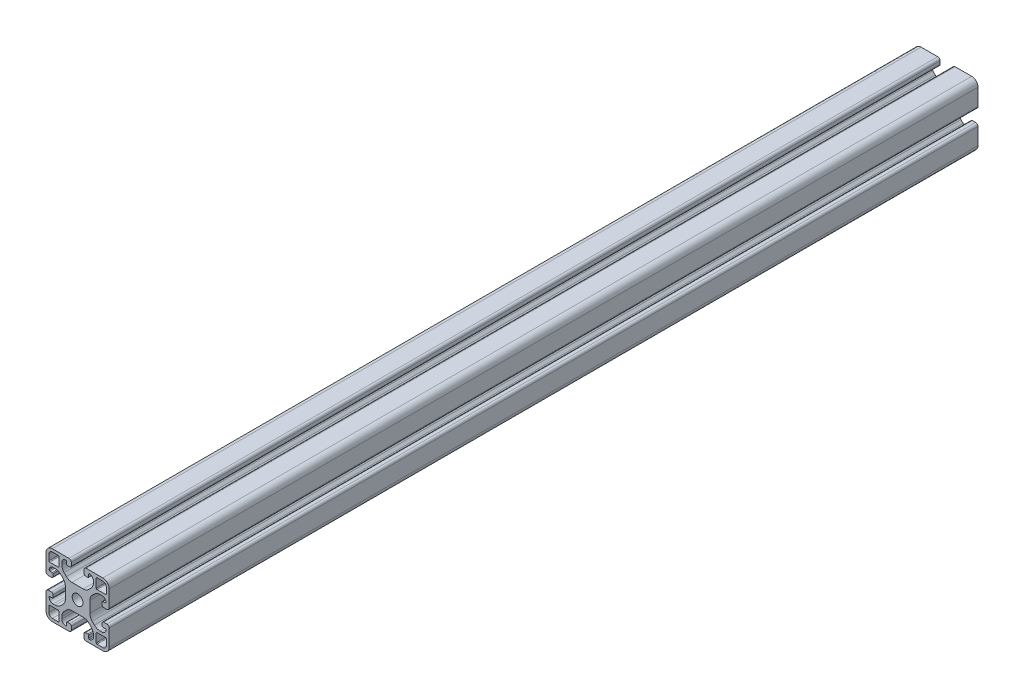
SolidWorks part; units mm, degrees
ref_plane "Plan de face" through (0, 0, 0) normal (0, 0, 1) x (1, 0, 0)
ref_plane "Plan de dessus" through (0, 0, 0) normal (0, 1, 0) x (1, 0, 0)
ref_plane "Plan de droite" through (0, 0, 0) normal (1, 0, 0) x (0, 0, -1)
ref_plane "Plan1" through (0, 0, -30) normal (0, 0, -1) x (-1, 0, 0)
sketch "Esquisse1" plane through (0, 0, -30) normal (0, 0, -1) x (-1, 0, 0)
  line L0 (-4.5, 15) -> (-4.5, 13.5)
  line L1 (-4, 13) -> (-2.5, 13)
  line L2 (-4.5, 10) -> (-5.8076, 10)
  line L3 (-9.3431, 11.4645) -> (-10.7855, 12.9069)
  line L4 (-12.25, 16.4424) -> (-12.25, 23.5576)
  line L5 (-10.7855, 27.0931) -> (-9.3431, 28.5355)
  line L6 (-5.8076, 30) -> (-4.5, 30)
  line L7 (-2.5, 27) -> (-4, 27)
  line L8 (-4.5, 26.5) -> (-4.5, 25)
  line L9 (-3.5, 24) -> (-1.5, 24)
  line L10 (0, 25.5) -> (0, 36)
  line L11 (-4, 40) -> (-14.5, 40)
  line L12 (-16, 38.5) -> (-16, 36.5)
  line L13 (-15, 35.5) -> (-13.5, 35.5)
  line L14 (-13, 36) -> (-13, 37.5)
  line L15 (-10, 35.5) -> (-10, 34.1924)
  line L16 (-11.4645, 30.6569) -> (-12.9069, 29.2145)
  line L17 (-16.4424, 27.75) -> (-23.5576, 27.75)
  line L18 (-27.0931, 29.2145) -> (-28.5355, 30.6569)
  line L19 (-30, 34.1924) -> (-30, 35.5)
  line L20 (-27, 37.5) -> (-27, 36)
  line L21 (-26.5, 35.5) -> (-25, 35.5)
  line L22 (-24, 36.5) -> (-24, 38.5)
  line L23 (-25.5, 40) -> (-36, 40)
  line L24 (-40, 36) -> (-40, 25.5)
  line L25 (-38.5, 24) -> (-36.5, 24)
  line L26 (-35.5, 25) -> (-35.5, 26.5)
  line L27 (-36, 27) -> (-37.5, 27)
  line L28 (-35.5, 30) -> (-34.1924, 30)
  line L29 (-30.6569, 28.5355) -> (-29.2145, 27.0931)
  line L30 (-27.75, 23.5576) -> (-27.75, 16.4424)
  line L31 (-29.2145, 12.9069) -> (-30.6569, 11.4645)
  line L32 (-34.1924, 10) -> (-35.5, 10)
  line L33 (-37.5, 13) -> (-36, 13)
  line L34 (-35.5, 13.5) -> (-35.5, 15)
  line L35 (-36.5, 16) -> (-38.5, 16)
  line L36 (-40, 14.5) -> (-40, 4)
  line L37 (-36, 0) -> (-25.5, 0)
  line L38 (-24, 1.5) -> (-24, 3.5)
  line L39 (-25, 4.5) -> (-26.5, 4.5)
  line L40 (-27, 4) -> (-27, 2.5)
  line L41 (-30, 4.5) -> (-30, 5.8076)
  line L42 (-28.5355, 9.3431) -> (-27.0931, 10.7855)
  line L43 (-23.5576, 12.25) -> (-16.4424, 12.25)
  line L44 (-12.9069, 10.7855) -> (-11.4645, 9.3431)
  line L45 (-10, 5.8076) -> (-10, 4.5)
  line L46 (-13, 2.5) -> (-13, 4)
  line L47 (-13.5, 4.5) -> (-15, 4.5)
  line L48 (-16, 3.5) -> (-16, 1.5)
  line L49 (-14.5, 0) -> (-4, 0)
  line L50 (0, 4) -> (0, 14.5)
  line L51 (-1.5, 16) -> (-3.5, 16)
  line L52 (-4, 1.8) -> (-7.7, 1.8)
  line L53 (-8.2, 2.3) -> (-8.2, 7.7)
  line L54 (-7.7, 8.2) -> (-2.3, 8.2)
  line L55 (-1.8, 7.7) -> (-1.8, 4)
  line L56 (-38.2, 4) -> (-38.2, 7.7)
  line L57 (-37.7, 8.2) -> (-32.3, 8.2)
  line L58 (-31.8, 7.7) -> (-31.8, 2.3)
  line L59 (-32.3, 1.8) -> (-36, 1.8)
  line L60 (-36, 38.2) -> (-32.3, 38.2)
  line L61 (-31.8, 37.7) -> (-31.8, 32.3)
  line L62 (-32.3, 31.8) -> (-37.7, 31.8)
  line L63 (-38.2, 32.3) -> (-38.2, 36)
  line L64 (-1.8, 36) -> (-1.8, 32.3)
  line L65 (-2.3, 31.8) -> (-7.7, 31.8)
  line L66 (-8.2, 32.3) -> (-8.2, 37.7)
  line L67 (-7.7, 38.2) -> (-4, 38.2)
  arc A0 (-4.5, 13.5) -> (-4, 13) centre (-4, 13.5) ccw
  arc A1 (-2.5, 13) -> (-2, 12.5) centre (-2.5, 12.5) cw
  arc A2 (-2, 12.5) -> (-4.5, 10) centre (-4.5, 12.5) cw
  arc A3 (-5.8076, 10) -> (-9.3431, 11.4645) centre (-5.8076, 15) cw
  arc A4 (-10.7855, 12.9069) -> (-12.25, 16.4424) centre (-7.25, 16.4424) cw
  arc A5 (-12.25, 23.5576) -> (-10.7855, 27.0931) centre (-7.25, 23.5576) cw
  arc A6 (-9.3431, 28.5355) -> (-5.8076, 30) centre (-5.8076, 25) cw
  arc A7 (-4.5, 30) -> (-2, 27.5) centre (-4.5, 27.5) cw
  arc A8 (-2, 27.5) -> (-2.5, 27) centre (-2.5, 27.5) cw
  arc A9 (-4, 27) -> (-4.5, 26.5) centre (-4, 26.5) ccw
  arc A10 (-4.5, 25) -> (-3.5, 24) centre (-3.5, 25) ccw
  arc A11 (-1.5, 24) -> (0, 25.5) centre (-1.5, 25.5) ccw
  arc A12 (0, 36) -> (-4, 40) centre (-4, 36) ccw
  arc A13 (-14.5, 40) -> (-16, 38.5) centre (-14.5, 38.5) ccw
  arc A14 (-16, 36.5) -> (-15, 35.5) centre (-15, 36.5) ccw
  arc A15 (-13.5, 35.5) -> (-13, 36) centre (-13.5, 36) ccw
  arc A16 (-13, 37.5) -> (-12.5, 38) centre (-12.5, 37.5) cw
  arc A17 (-12.5, 38) -> (-10, 35.5) centre (-12.5, 35.5) cw
  arc A18 (-10, 34.1924) -> (-11.4645, 30.6569) centre (-15, 34.1924) cw
  arc A19 (-12.9069, 29.2145) -> (-16.4424, 27.75) centre (-16.4424, 32.75) cw
  arc A20 (-23.5576, 27.75) -> (-27.0931, 29.2145) centre (-23.5576, 32.75) cw
  arc A21 (-28.5355, 30.6569) -> (-30, 34.1924) centre (-25, 34.1924) cw
  arc A22 (-30, 35.5) -> (-27.5, 38) centre (-27.5, 35.5) cw
  arc A23 (-27.5, 38) -> (-27, 37.5) centre (-27.5, 37.5) cw
  arc A24 (-27, 36) -> (-26.5, 35.5) centre (-26.5, 36) ccw
  arc A25 (-25, 35.5) -> (-24, 36.5) centre (-25, 36.5) ccw
  arc A26 (-24, 38.5) -> (-25.5, 40) centre (-25.5, 38.5) ccw
  arc A27 (-36, 40) -> (-40, 36) centre (-36, 36) ccw
  arc A28 (-40, 25.5) -> (-38.5, 24) centre (-38.5, 25.5) ccw
  arc A29 (-36.5, 24) -> (-35.5, 25) centre (-36.5, 25) ccw
  arc A30 (-35.5, 26.5) -> (-36, 27) centre (-36, 26.5) ccw
  arc A31 (-37.5, 27) -> (-38, 27.5) centre (-37.5, 27.5) cw
  arc A32 (-38, 27.5) -> (-35.5, 30) centre (-35.5, 27.5) cw
  arc A33 (-34.1924, 30) -> (-30.6569, 28.5355) centre (-34.1924, 25) cw
  arc A34 (-29.2145, 27.0931) -> (-27.75, 23.5576) centre (-32.75, 23.5576) cw
  arc A35 (-27.75, 16.4424) -> (-29.2145, 12.9069) centre (-32.75, 16.4424) cw
  arc A36 (-30.6569, 11.4645) -> (-34.1924, 10) centre (-34.1924, 15) cw
  arc A37 (-35.5, 10) -> (-38, 12.5) centre (-35.5, 12.5) cw
  arc A38 (-38, 12.5) -> (-37.5, 13) centre (-37.5, 12.5) cw
  arc A39 (-36, 13) -> (-35.5, 13.5) centre (-36, 13.5) ccw
  arc A40 (-35.5, 15) -> (-36.5, 16) centre (-36.5, 15) ccw
  arc A41 (-38.5, 16) -> (-40, 14.5) centre (-38.5, 14.5) ccw
  arc A42 (-40, 4) -> (-36, 0) centre (-36, 4) ccw
  arc A43 (-25.5, 0) -> (-24, 1.5) centre (-25.5, 1.5) ccw
  arc A44 (-24, 3.5) -> (-25, 4.5) centre (-25, 3.5) ccw
  arc A45 (-26.5, 4.5) -> (-27, 4) centre (-26.5, 4) ccw
  arc A46 (-27, 2.5) -> (-27.5, 2) centre (-27.5, 2.5) cw
  arc A47 (-27.5, 2) -> (-30, 4.5) centre (-27.5, 4.5) cw
  arc A48 (-30, 5.8076) -> (-28.5355, 9.3431) centre (-25, 5.8076) cw
  arc A49 (-27.0931, 10.7855) -> (-23.5576, 12.25) centre (-23.5576, 7.25) cw
  arc A50 (-16.4424, 12.25) -> (-12.9069, 10.7855) centre (-16.4424, 7.25) cw
  arc A51 (-11.4645, 9.3431) -> (-10, 5.8076) centre (-15, 5.8076) cw
  arc A52 (-10, 4.5) -> (-12.5, 2) centre (-12.5, 4.5) cw
  arc A53 (-12.5, 2) -> (-13, 2.5) centre (-12.5, 2.5) cw
  arc A54 (-13, 4) -> (-13.5, 4.5) centre (-13.5, 4) ccw
  arc A55 (-15, 4.5) -> (-16, 3.5) centre (-15, 3.5) ccw
  arc A56 (-16, 1.5) -> (-14.5, 0) centre (-14.5, 1.5) ccw
  arc A57 (-4, 0) -> (0, 4) centre (-4, 4) ccw
  arc A58 (0, 14.5) -> (-1.5, 16) centre (-1.5, 14.5) ccw
  arc A59 (-3.5, 16) -> (-4.5, 15) centre (-3.5, 15) ccw
  circle A60 centre (-20, 20) radius 3.4
  arc A61 (-1.8, 4) -> (-4, 1.8) centre (-4, 4) cw
  arc A62 (-7.7, 1.8) -> (-8.2, 2.3) centre (-7.7, 2.3) cw
  arc A63 (-8.2, 7.7) -> (-7.7, 8.2) centre (-7.7, 7.7) cw
  arc A64 (-2.3, 8.2) -> (-1.8, 7.7) centre (-2.3, 7.7) cw
  arc A65 (-36, 1.8) -> (-38.2, 4) centre (-36, 4) cw
  arc A66 (-38.2, 7.7) -> (-37.7, 8.2) centre (-37.7, 7.7) cw
  arc A67 (-32.3, 8.2) -> (-31.8, 7.7) centre (-32.3, 7.7) cw
  arc A68 (-31.8, 2.3) -> (-32.3, 1.8) centre (-32.3, 2.3) cw
  arc A69 (-38.2, 36) -> (-36, 38.2) centre (-36, 36) cw
  arc A70 (-32.3, 38.2) -> (-31.8, 37.7) centre (-32.3, 37.7) cw
  arc A71 (-31.8, 32.3) -> (-32.3, 31.8) centre (-32.3, 32.3) cw
  arc A72 (-37.7, 31.8) -> (-38.2, 32.3) centre (-37.7, 32.3) cw
  arc A73 (-4, 38.2) -> (-1.8, 36) centre (-4, 36) cw
  arc A74 (-1.8, 32.3) -> (-2.3, 31.8) centre (-2.3, 32.3) cw
  arc A75 (-7.7, 31.8) -> (-8.2, 32.3) centre (-7.7, 32.3) cw
  arc A76 (-8.2, 37.7) -> (-7.7, 38.2) centre (-7.7, 37.7) cw
extrude "Boss.-Extru.1" add sketch "Esquisse1" against normal blind 550
